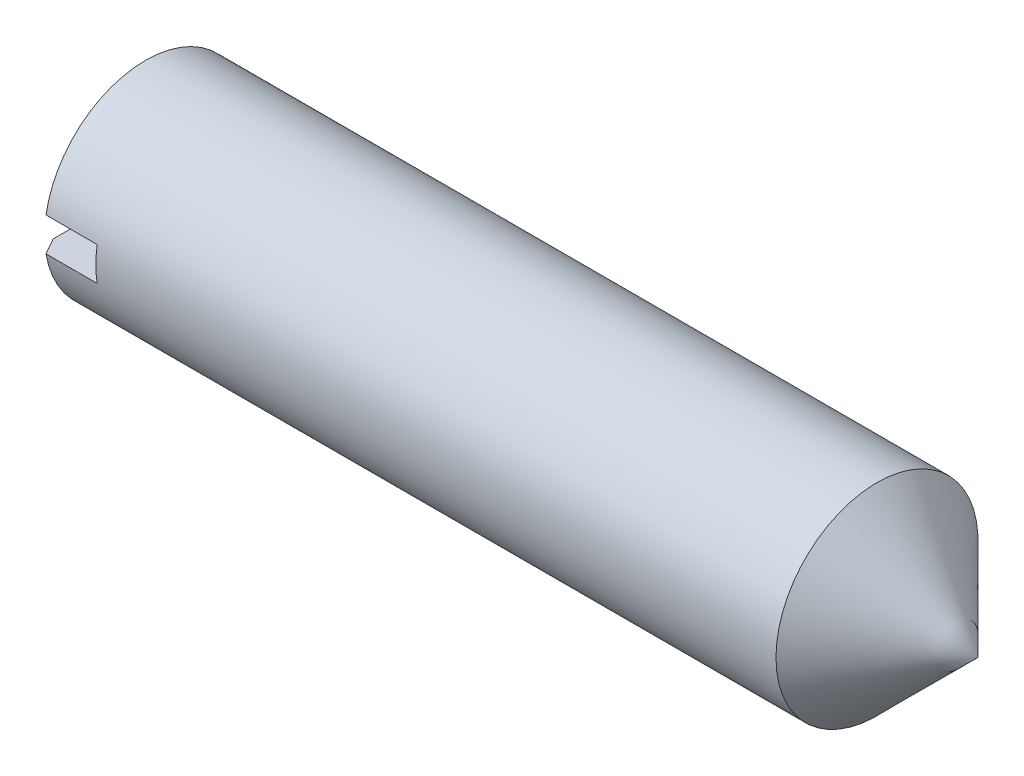
SolidWorks part; units mm, degrees
revolve "BaseBody" add sketch "BodySke"
sketch "BodySke" plane through (0, 0, 0) normal (0, 0, 1) x (1, 0, 0)
  line L0 (0, 0) -> (0, 5.036)
  line L1 (0, 5.036) -> (0.5566, 6)
  line L2 (0.5566, 6) -> (44, 6)
  line L3 (44, 6) -> (50, 0)
  line L4 (50, 0) -> (0, 0)
  line L5 (-12.7, 0) -> (88.9, 0) construction
  line L6 (44, -6) -> (50, 0) construction
  line L7 (0.875, 15.875) -> (0.875, -3.175) construction
  line L8 (0, -5.036) -> (0.5566, -6) construction
  dimension "Drive_ch_ang" = 60
cosmetic thread "ThreadCosmetic" [suppressed]
extrude "Slot" cut sketch "Sketch2" against normal blind 3.6
sketch "Sketch2" plane through (0, 0, 0) normal (-1, 0, 0) x (0, 0, 1)
  line L0 (6, 1) -> (-6, 1)
  line L1 (6, -1) -> (6, 1)
  line L2 (-6, -1) -> (-6, 1)
  line L4 (6, -1) -> (-6, -1)
  circle A2 centre (0, 0) radius 6 construction
  dimension "D1" = 0.2
  dimension "Slot_width" = 2
ref_plane "Plane1" through (0, 0, 0) normal (0, 0, 1) x (1, 0, 0)
ref_plane "Plane2" through (0, 0, 0) normal (0, 1, 0) x (1, 0, 0)
ref_plane "Plane3" through (0, 0, 0) normal (1, 0, 0) x (0, 0, -1)
sketch "ThdSchSke" plane through (0, 0, 0) normal (0, 0, 1) x (1, 0, 0)
  line L0 (0.5566, -5.036) -> (-0.1184, -6)
  line L1 (0.5566, -5.036) -> (1.2316, -6)
  line L2 (1.2316, -6) -> (1.2316, -7.5)
  line L3 (-3.175, 0) -> (5.1513, 0) construction
  line L4 (0.5566, 6) -> (0.5566, -6) construction
  line L5 (1.2316, -7.5) -> (-0.1184, -7.5)
  line L6 (-0.1184, -7.5) -> (-0.1184, -6)
  dimension "Thread_minor" = 1.993
  dimension "Diameter" = 2.5
revolve "ThreadSchematic" [suppressed] cut sketch "ThdSchSke" angle 360 about L3
pattern_linear "ThdSchPat" [suppressed]
equation "\"Thread_minor@ThreadCosmetic\" = \"Minor_dia@BodySke\""
equation "\"Thread_minor@ThdSchSke\" = \"Thread_minor@ThreadCosmetic\""
equation "\"Diameter@ThdSchSke\" = \"Diameter@BodySke\""
equation "\"Overcut@ThdSchSke\" = \"Diameter@BodySke\" * 1.25"
equation "\"Num_threads@ThdSchPat\" = int( (\"Length@BodySke\" - ( ( ( \"Diameter@BodySke\" - \"Minor_dia@BodySke\" ) * 0.5 ) / tan( \"Drive_ch_ang@BodySke\" * 0.017453292 ) ) - ( ( \"Diameter@BodySke\" * 0.5 ) / tan( \"Cone_ang@BodySke\" * 0.008726646 ) ) ) / \"Advance@BodySke\" + 0.999 )  + 1"
equation "\"Advance@ThdSchPat\" = (\"Length@BodySke\" - ( ( ( \"Diameter@BodySke\" - \"Minor_dia@BodySke\" ) * 0.5 ) / tan( \"Drive_ch_ang@BodySke\" * 0.017453292 ) ) - ( ( \"Diameter@BodySke\" * 0.5 ) / tan( \"Cone_ang@BodySke\" * 0.008726646 ) ) ) /  (\"Num_threads@ThdSchPat\" - 1) 'relax it"
equation "' \"Num_threads@ThdSchPat\" = \"Num_threads@ThdSchPat\" - sgn( \"Num_threads@ThdSchPat\" - 1) '---chamfered tips only---"
equation "\"D1@Sketch2\" = \"Slot_width@Sketch2\" / 2"
